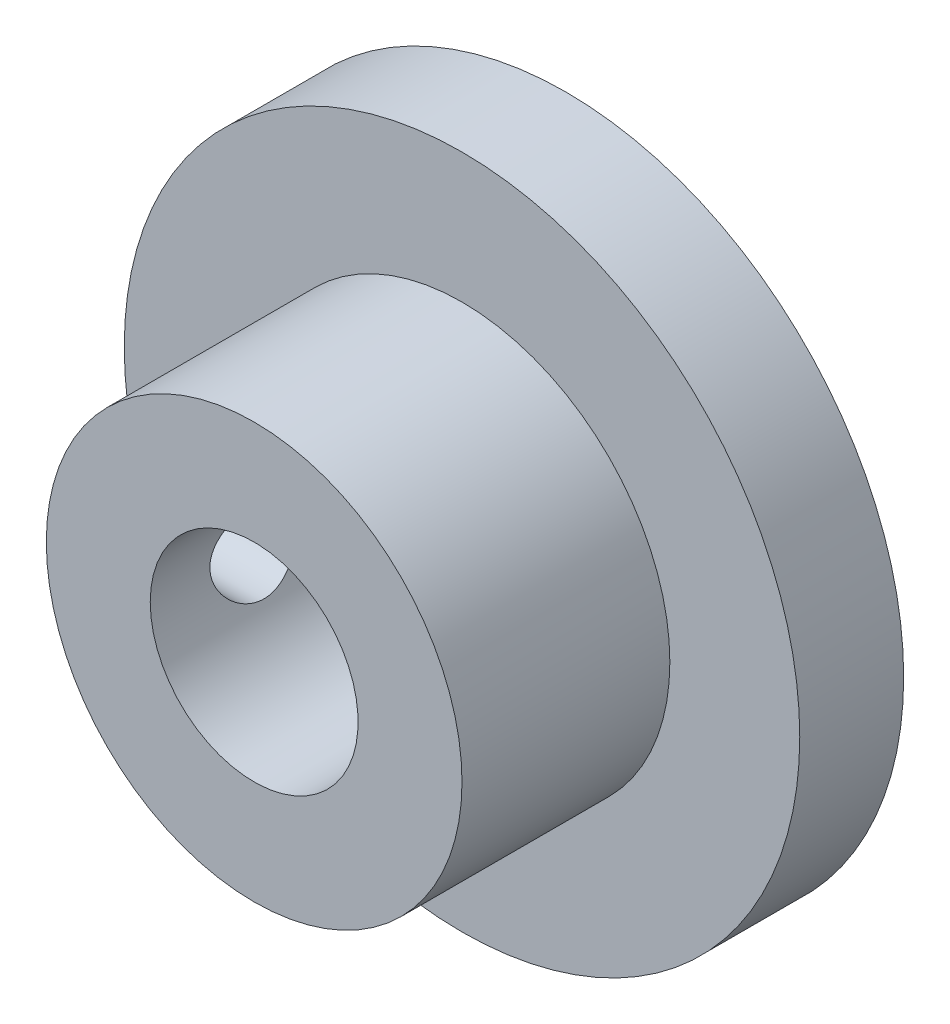
SolidWorks part; units mm, degrees
material "303 Stainless"
ref_plane "Front Plane" through (0, 0, 0) normal (0, 0, 1) x (1, 0, 0)
ref_plane "Top Plane" through (0, 0, 0) normal (0, 1, 0) x (1, 0, 0)
ref_plane "Right Plane" through (0, 0, 0) normal (1, 0, 0) x (0, 0, -1)
sketch "Sketch1" plane through (0, 0, 0) normal (0, 0, 1) x (1, 0, 0)
  circle A0 centre (0, 0) radius 10.3187
  dimension "D1" = 20.6375
extrude "Boss-Extrude1" add sketch "Sketch1" along normal blind 3.175
sketch "Sketch2" plane through (0, 0, 3.175) normal (0, 0, 1) x (1, 0, 0)
  circle A0 centre (0, 0) radius 6.35
  dimension "D1" = 12.7
extrude "Boss-Extrude2" add sketch "Sketch2" along normal blind 6.35
sketch "Sketch3" plane through (0, 0, 0) normal (0, 0, -1) x (-1, 0, 0)
  circle A0 centre (0, 0) radius 3.175
  dimension "D1" = 6.35
extrude "Cut-Extrude1" cut sketch "Sketch3" against normal through all
ref_plane "Plane1" through (-6.35, 0, 0) normal (-1, 0, 0) x (0, 0, 1)
hole_wizard "#6-32 Tapped Hole1" positions "Sketch4" profile "Sketch5" tap size "#6-32" standard "ANSI Inch"
sketch "Sketch4" plane through (-6.35, 0, 0) normal (-1, 0, 0) x (0, 0, 1)
  line L0 (9.525, -6.35) -> (9.525, 6.35) construction
  line L1 (9.525, -6.35) -> (9.525, 6.35) construction
  line L2 (3.175, -10.3187) -> (3.175, 10.3187) construction
  line L3 (3.175, -10.3187) -> (3.175, 10.3187) construction
  line L4 (9.525, 0) -> (3.175, 0) construction
  point P0 (6.35, 0)
  point P10 (6.35, 0)
sketch "Sketch5" plane through (-6.35, 0, 6.35) normal (0, 1, 0) x (0, 0, 1)
  line L0 (0, 0) -> (0, 3.175)
  line L1 (0, 3.175) -> (1.3525, 3.175)
  line L2 (1.3525, 3.175) -> (1.3525, 0)
  line L5 (1.3525, 0) -> (0, 0)
  line L11 (0, -6.35) -> (0, 107.95) construction
  dimension "Thru Tap Drill Dia." = 2.7051
  dimension "Thru Tap Drill Depth" = 3.175
cosmetic thread "Hole Thread1" parameters "D2"=3.5052
equation "\"hub\"= .5"
equation "\"bore\"= .25"
equation "\"hub l\"= .25"
equation "\"pitch\"= .8125"
equation "\"D1@Sketch1\"=\"pitch\""
equation "\"D1@Sketch2\"=\"hub\""
equation "\"D1@Sketch3\"=\"bore\""
equation "\"face\"= .125"
equation "\"D1@Boss-Extrude1\"=\"face\""
equation "\"D1@Boss-Extrude2\"=\"hub l\""
